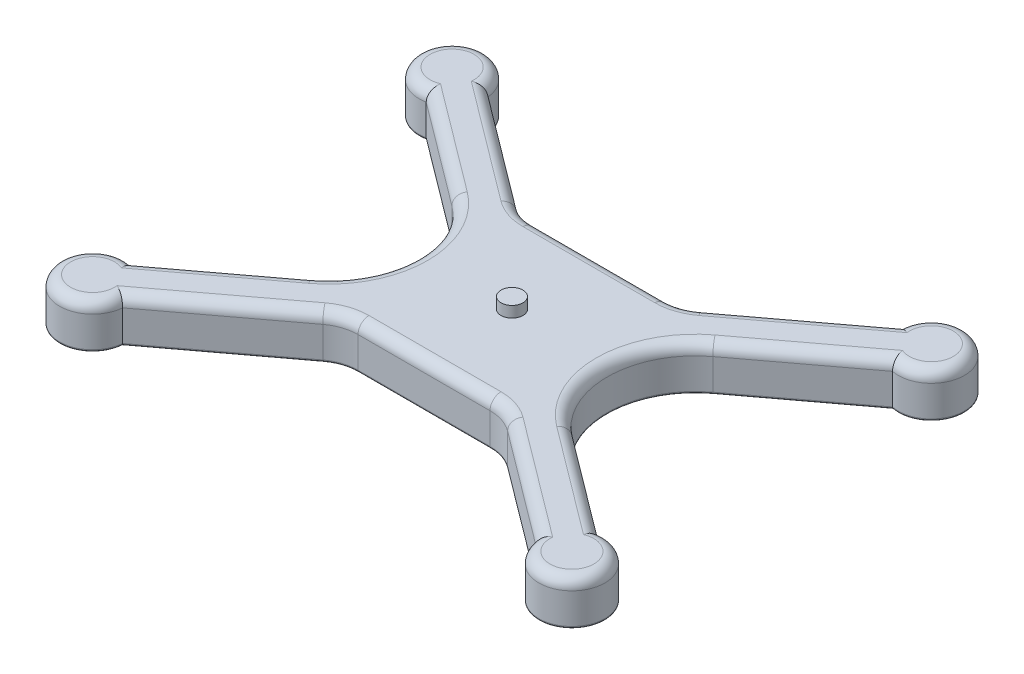
SolidWorks part; units mm, degrees
ref_plane "Front Plane" through (0, 0, 0) normal (0, 0, 1) x (1, 0, 0)
ref_plane "Top Plane" through (0, 0, 0) normal (0, 1, 0) x (1, 0, 0)
ref_plane "Right Plane" through (0, 0, 0) normal (1, 0, 0) x (0, 0, -1)
sketch "Sketch1" plane through (0, 0, 0) normal (0, 1, 0) x (1, 0, 0)
  line L0 (-50, 37.5) -> (50, -37.5) construction
  line L1 (-50, -37.5) -> (50, 37.5) construction
  line L2 (-53, 33.5) -> (47, -41.5)
  line L3 (-47, -41.5) -> (53, 33.5)
  line L4 (-47, 41.5) -> (53, -33.5)
  line L5 (-53, -33.5) -> (47, 41.5)
  line L6 (-55, 0) -> (55, 0) construction
  line L7 (0, -55) -> (0, 55) construction
  line L8 (-18.3333, 20) -> (18.3333, 20)
  line L9 (-18.3333, -20) -> (18.3333, -20)
  circle A0 centre (-54.4721, 40.8541) radius 7.5
  circle A1 centre (-54.4721, -40.8541) radius 7.5
  circle A2 centre (54.4721, -40.8541) radius 7.5
  circle A3 centre (54.4721, 40.8541) radius 7.5
  point P4 (0, 0)
  point P30 (0, 20)
  point P31 (0, -20)
  dimension "D5" = 15
  dimension "D6" = 40
  dimension "D1" = 100
  dimension "D2" = 75
  dimension "D3" = 5
  dimension "D4" = 5
extrude "Boss-Extrude1" add sketch "Sketch1" along normal blind 10 contours L8 L4 L5 | A0 L2 L5 L4 | L5 L2 L3 L4 | L3 A3 L5 L4 | A2 L4 L3 L2 | L3 L9 L2 | L5 A1 L3 L2 | A0 | A1 | A2 | A3
fillet "Fillet1" radius 20 2 edges at (8.3333, 5, 0) (-8.3333, 5, 0)
sketch "Sketch2" plane through (0, 10, 0) normal (0, 1, 0) x (1, 0, 0)
  circle A0 centre (0, 0) radius 2.5
  dimension "D1" = 5
extrude "Boss-Extrude2" add sketch "Sketch2" along normal blind 2.5
fillet "Fillet2" radius 10 4 edges at (18.3333, 5, 20) (-18.3333, 5, 20) (18.3333, 5, -20) (-18.3333, 5, -20)
fillet "Fillet4" radius 2.5 20 edges at (18.1623, 10, -20.5132) (34, 10, -31.75) (60.4721, 10, -45.3541) (41.3333, 10, -24.75) (21.6667, 10, 0) (41.3333, 10, 24.75) (60.4721, 10, 45.3541) (34, 10, 31.75) (18.1623, 10, 20.5132) (0, 10, 20) (-18.1623, 10, 20.5132) (-34, 10, 31.75) (-60.4721, 10, 45.3541) (-41.3333, 10, 24.75) (-21.6667, 10, 0) (-41.3333, 10, -24.75) (-60.4721, 10, -45.3541) (-34, 10, -31.75) (-18.1623, 10, -20.5132) (0, 10, -20)
fillet "Fillet5" radius 0.5 20 edges at (-60.4721, 0, -45.3541) (-41.3333, 0, -24.75) (-21.6667, 0, 0) (-41.3333, 0, 24.75) (-60.4721, 0, 45.3541) (-34, 0, 31.75) (-18.1623, 0, 20.5132) (0, 0, 20) (18.1623, 0, 20.5132) (34, 0, 31.75) (60.4721, 0, 45.3541) (41.3333, 0, 24.75) (21.6667, 0, 0) (41.3333, 0, -24.75) (60.4721, 0, -45.3541) (34, 0, -31.75) (18.1623, 0, -20.5132) (0, 0, -20) (-18.1623, 0, -20.5132) (-34, 0, -31.75)
